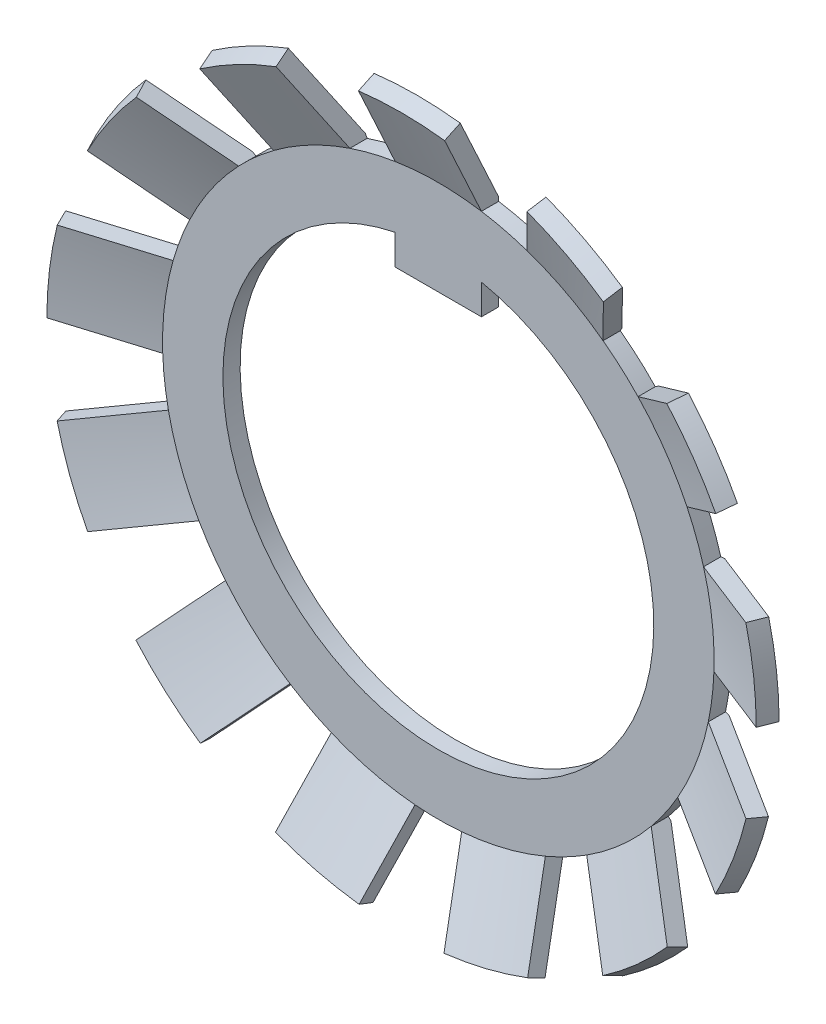
SolidWorks part; units mm, degrees
revolve "Base-Revolve" add sketch "Sketch1" angle 360 about L6
sketch "Sketch1" plane through (0, 0, 0) normal (1, 0, 0) x (0, 0, -1)
  line L0 (0, 12.5) -> (0, 16.2217)
  line L1 (0, 16.2217) -> (-2.2282, 21)
  line L2 (-1, 16) -> (-3.1345, 20.5774)
  line L3 (-1, 12.5) -> (-1, 16)
  line L4 (-3.1345, 20.5774) -> (-2.2282, 21)
  line L5 (-1, 12.5) -> (0, 12.5)
  line L6 (-14, 0) -> (12, 0) construction
  dimension "d3" = 25
  dimension "Tab Angle" = 25
  dimension "d5" = 42
  dimension "d4" = 32
  dimension "B1" = 1
ref_plane "Plane1" through (0, 0, 0) normal (0, 0, 1) x (1, 0, 0)
ref_plane "Plane2" through (0, 0, 0) normal (0, 1, 0) x (1, 0, 0)
ref_plane "Plane3" through (0, 0, 0) normal (1, 0, 0) x (0, 0, -1)
sketch "Sketch3" plane through (0, 0, 0) normal (0, 0, -1) x (-1, 0, 0)
  line L0 (0, 0) -> (0, 40) construction
  line L1 (0, 0) -> (-12.8597, 24.5021) construction
  line L2 (-2.5, 15.8035) -> (-2.5, 20.8507)
  line L3 (-5.1306, 15.1551) -> (-7.4761, 19.6241)
  line L4 (-2.5, 20.8507) -> (-7.4761, 19.6241) construction
  line L5 (0, 0) -> (-4.9881, 20.2374) construction
  circle A0 centre (0, 0) radius 16 construction
  circle A1 centre (0, 0) radius 21 construction
  arc A2 (-2.5, 15.8035) -> (-5.1306, 15.1551) centre (0, 0) ccw
  arc A3 (-2.5, 20.8507) -> (-7.4761, 19.6241) centre (0, 0) ccw
  dimension "D3" = 5
  dimension "D1" = 13.846
extrude "Cut-Extrude2" cut sketch "Sketch3" against normal through all
pattern_circular "CirPattern1" count 13 over 360 about axis through (0, 0, 0) along (0, 0, 1) of "Cut-Extrude2"
sketch "Sketch4" plane through (0, 0, 0) normal (0, 0, -1) x (-1, 0, 0)
  line L2 (-2.5, 12.2474) -> (-2.5, 10.5)
  line L3 (2.5, 10.5) -> (2.5, 12.2474)
  line L4 (-2.5, 10.5) -> (2.5, 10.5)
  line L7 (0, 0) -> (0, 22) construction
  line L9 (-2.5, 15.8035) -> (-2.5, 20.8507) construction
  circle A0 centre (0, 0) radius 12.5 construction
  circle A2 centre (0, 0) radius 12.5
  arc A3 (2.5, 12.2474) -> (-2.5, 12.2474) centre (0, 0) ccw
  dimension "M" = 23
  dimension "D2" = 0
extrude "Boss-Extrude1" add sketch "Sketch4" along normal up to surface (1 mm away)
equation "\"D1@Sketch3\" = (360/\"No Tabs@CirPattern1\")/2"
equation "\"D3@Sketch3\"=\"f@Sketch3\""
